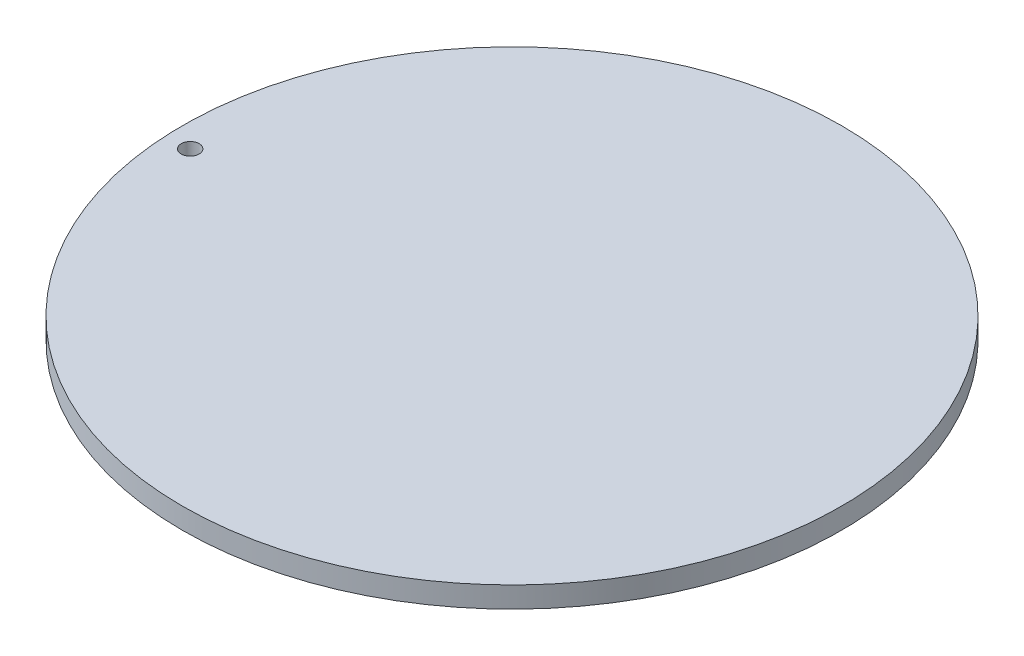
SolidWorks part; units mm, degrees
ref_plane "Plan de face" through (0, 0, 0) normal (0, 0, 1) x (1, 0, 0)
ref_plane "Plan de dessus" through (0, 0, 0) normal (0, 1, 0) x (1, 0, 0)
ref_plane "Plan de droite" through (0, 0, 0) normal (1, 0, 0) x (0, 0, -1)
sketch "Esquisse1" plane through (0, 0, 0) normal (0, 0, 1) x (1, 0, 0)
  line L0 (0, 25.133) -> (0, -30.4295) construction
  line L1 (0, 4.3518) -> (110, 4.3518)
  line L2 (110, 4.3518) -> (110, -2.6482)
  line L3 (110, -2.6482) -> (0, -2.6482)
  line L4 (0, 4.3518) -> (0, -2.6482)
  dimension "D1" = 7
  dimension "D2" = 110
revolve "Révolution1" add sketch "Esquisse1" angle 360 about L0
sketch "Esquisse6" plane through (0, 4.3518, 0) normal (0, 1, 0) x (1, 0, 0)
  circle A0 centre (-102, -5.4151) radius 3
  circle A1 centre (0, 0) radius 110 construction
  dimension "D1" = 6
  dimension "D2" = 102
extrude "Enlèv. mat.-Extru.1" cut sketch "Esquisse6" against normal blind 10
